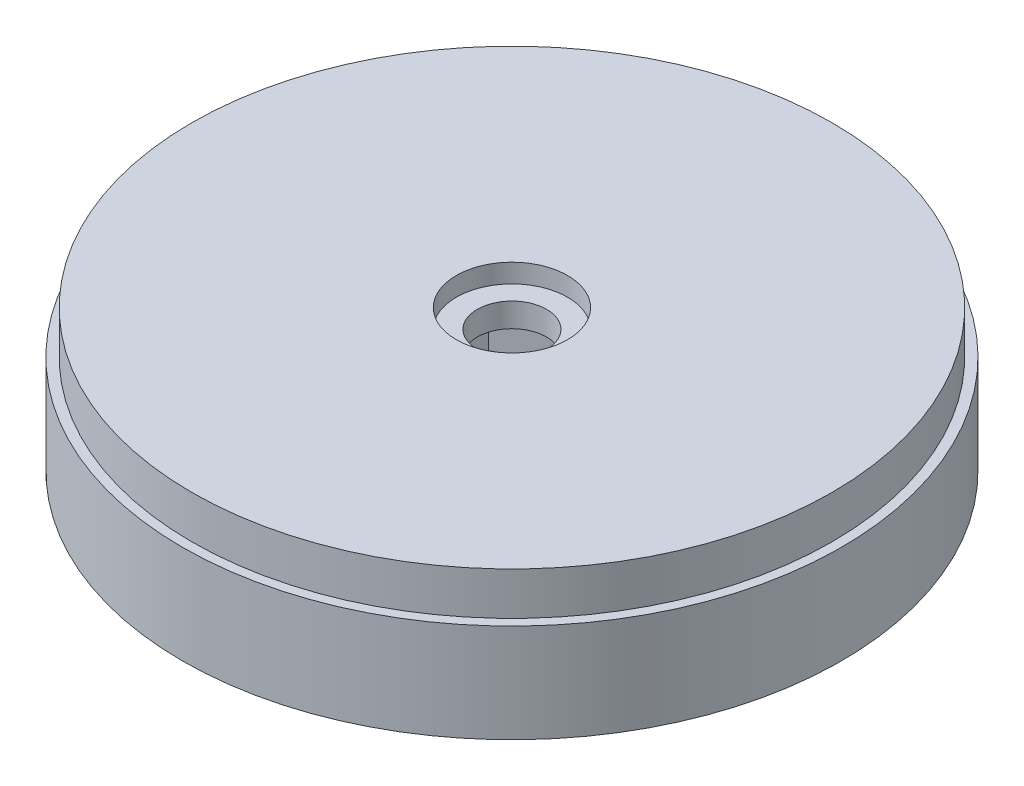
SolidWorks part; units mm, degrees
ref_plane "Front Plane" through (0, 0, 0) normal (0, 0, 1) x (1, 0, 0)
ref_plane "Top Plane" through (0, 0, 0) normal (0, 1, 0) x (1, 0, 0)
ref_plane "Right Plane" through (0, 0, 0) normal (1, 0, 0) x (0, 0, -1)
sketch "Sketch1" plane through (0, 0, 0) normal (0, 1, 0) x (1, 0, 0)
  line L1 (0, 7.5056) -> (-6.5, 3.7528)
  line L2 (-6.5, 3.7528) -> (-6.5, -3.7528)
  line L3 (-6.5, -3.7528) -> (0, -7.5056)
  line L4 (0, -7.5056) -> (6.5, -3.7528)
  line L5 (6.5, -3.7528) -> (6.5, 3.7528)
  line L6 (6.5, 3.7528) -> (0, 7.5056)
  circle A0 centre (0, 0) radius 38.5
  circle A1 centre (0, 0) radius 6.5 construction
  dimension "D1" = 77
  dimension "D2" = 13
extrude "Boss-Extrude1" add sketch "Sketch1" along normal blind 11.5
sketch "Sketch2" plane through (0, 11.5, 0) normal (0, 1, 0) x (1, 0, 0)
  circle A0 centre (0, 0) radius 4.05
  circle A1 centre (0, 0) radius 37.4
  circle A2 centre (0, 0) radius 38.5 construction
  dimension "D1" = 8.1
  dimension "D2" = 1.1
extrude "Boss-Extrude2" add sketch "Sketch2" along normal blind 5
sketch "Sketch3" plane through (0, 0, 0) normal (0, -1, 0) x (1, 0, 0)
  circle A0 centre (0, 0) radius 8
  dimension "D1" = 16
extrude "Cut-Extrude1" cut sketch "Sketch3" against normal blind 7
sketch "Sketch4" plane through (0, 16.5, 0) normal (0, 1, 0) x (1, 0, 0)
  circle A0 centre (0, 0) radius 6.5
  dimension "D1" = 13
extrude "Cut-Extrude2" cut sketch "Sketch4" against normal blind 2.2
